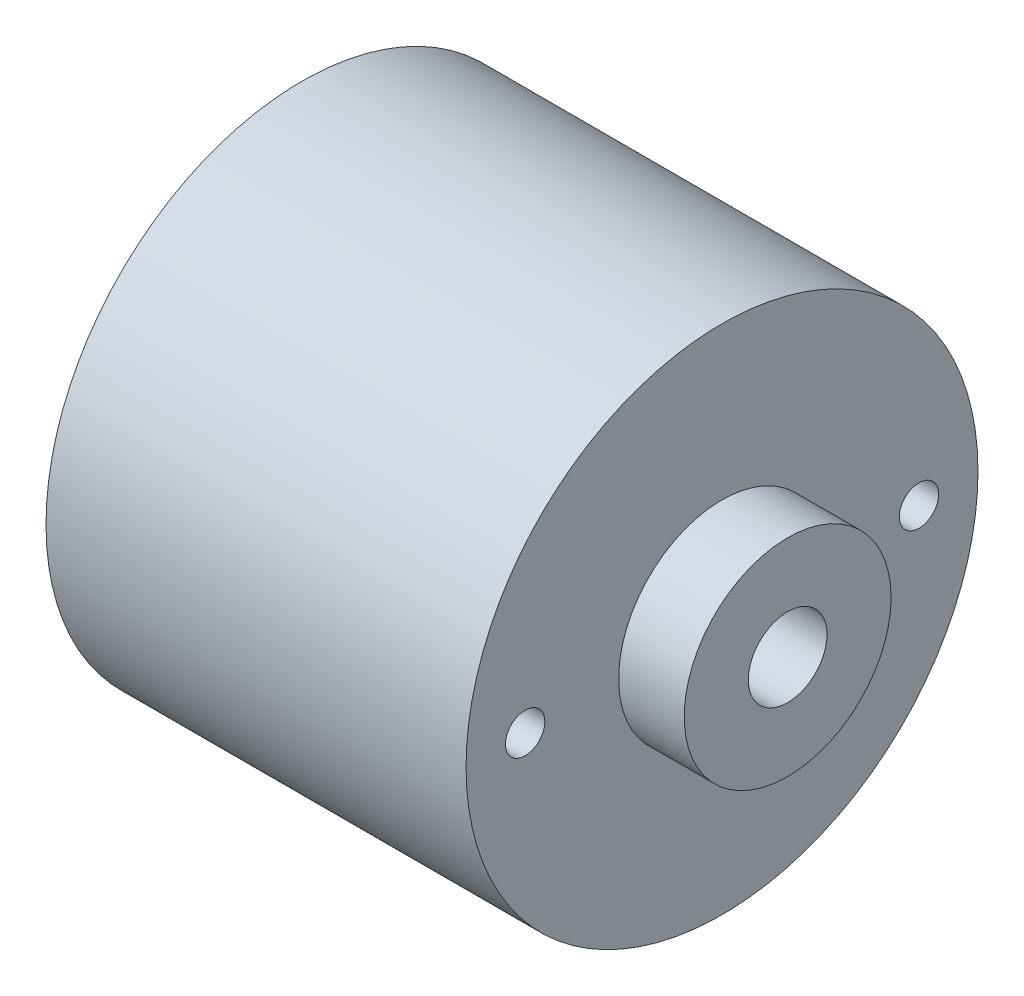
SolidWorks part; units mm, degrees
ref_plane "前视基准面" through (0, 0, 0) normal (0, 0, 1) x (1, 0, 0)
ref_plane "上视基准面" through (0, 0, 0) normal (0, 1, 0) x (1, 0, 0)
ref_plane "右视基准面" through (0, 0, 0) normal (1, 0, 0) x (0, 0, -1)
other "Configuration Table"
sketch "草图1" plane through (0, 0, 0) normal (1, 0, 0) x (0, 0, -1)
  circle A0 centre (0, 0) radius 19.5
  dimension "D1" = 39
extrude "凸台-拉伸1" add sketch "草图1" along normal blind 32
sketch "草图2" plane through (32, 0, 0) normal (1, 0, 0) x (0, 0, -1)
  circle A0 centre (0, 0) radius 7.88
  dimension "D1" = 15.76
extrude "凸台-拉伸2" add sketch "草图2" along normal blind 5
sketch "草图3" plane through (37, 0, 0) normal (1, 0, 0) x (0, 0, -1)
  circle A0 centre (0, 0) radius 3
  dimension "D1" = 6
extrude "切除-拉伸1" cut sketch "草图3" against normal up to next
sketch "草图4" plane through (32, 0, 0) normal (1, 0, 0) x (0, 0, -1)
  line L0 (0, 0) -> (16.6367, 0) construction
  circle A0 centre (15, 0) radius 1.5
  circle A1 centre (-15, 0) radius 1.5
  dimension "D2" = 3
  dimension "D3" = 3
  dimension "D1" = 15
  dimension "D4" = 15
extrude "切除-拉伸2" cut sketch "草图4" against normal blind 10
